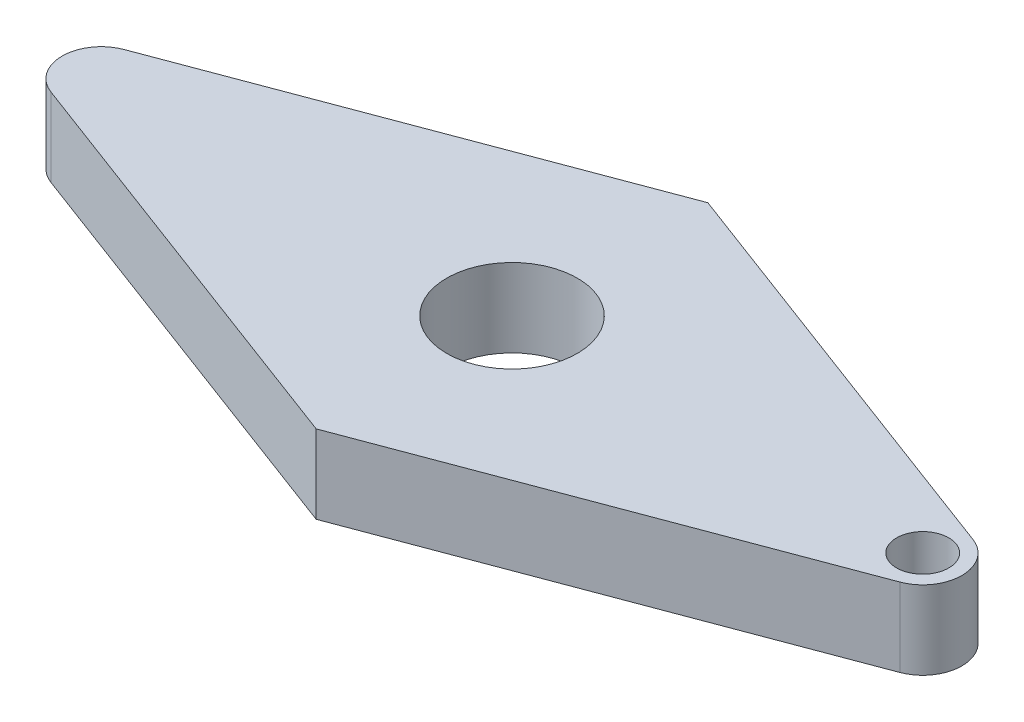
SolidWorks part; units mm, degrees
ref_plane "前基準面" through (0, 0, 0) normal (0, 0, 1) x (1, 0, 0)
ref_plane "上基準面" through (0, 0, 0) normal (0, 1, 0) x (1, 0, 0)
ref_plane "右基準面" through (0, 0, 0) normal (1, 0, 0) x (0, 0, -1)
sketch "草圖1" plane through (0, 0, 0) normal (0, 1, 0) x (1, 0, 0)
  line L0 (-20, 0) -> (20, 0) construction
  line L1 (0, 7.5) -> (0, -7.5) construction
  line L2 (-16.2547, 1.4045) -> (0, 7.5)
  line L3 (0, 7.5) -> (16.2547, 1.4045)
  line L4 (16.2547, -1.4045) -> (0, -7.5)
  line L5 (0, -7.5) -> (-16.2547, -1.4045)
  circle A0 centre (0, 0) radius 2.5
  arc A1 (-16.2547, -1.4045) -> (-16.2547, 1.4045) centre (-15.728, 0) cw
  arc A2 (16.2547, -1.4045) -> (16.2547, 1.4045) centre (15.728, 0) ccw
  point P6 (0, 0)
  point P9 (0, 0)
  dimension "D3" = 5
  dimension "D4" = 1.5
  dimension "D5" = 1.5
  dimension "D1" = 40
  dimension "D2" = 15
extrude "填料-伸長1" add sketch "草圖1" along normal blind 3
sketch "草圖3" plane through (0, 3, 0) normal (0, 1, 0) x (1, 0, 0)
  circle A0 centre (15.728, 0) radius 1
  dimension "D1" = 2
extrude "除料-伸長1" cut sketch "草圖3" against normal through all
